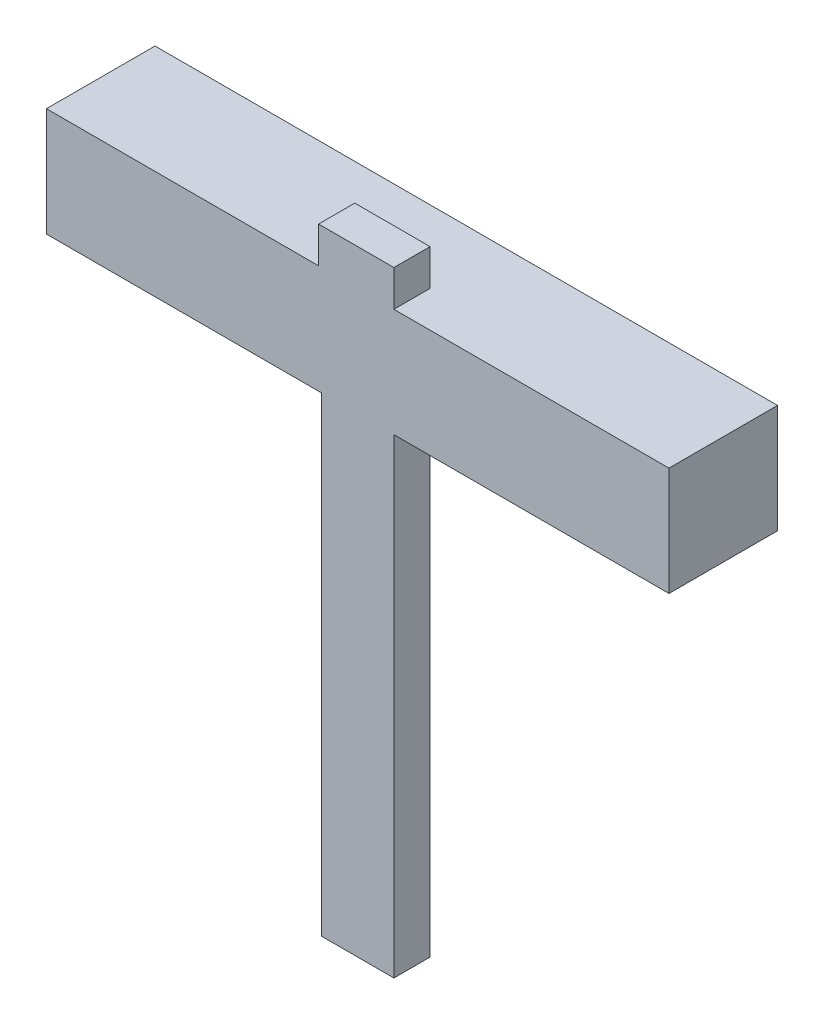
SolidWorks part; units mm, degrees
ref_plane "Front Plane" through (0, 0, 0) normal (0, 0, 1) x (1, 0, 0)
ref_plane "Top Plane" through (0, 0, 0) normal (0, 1, 0) x (1, 0, 0)
ref_plane "Right Plane" through (0, 0, 0) normal (1, 0, 0) x (0, 0, -1)
sketch "Sketch1" plane through (0, 0, 0) normal (0, 0, 1) x (1, 0, 0)
  line L0 (5, 0) -> (40, 0) construction
  line L1 (40, 0) -> (5, 0) construction
  line L2 (-5, 0) -> (-40, 0) construction
  line L3 (0, 0) -> (0, 5) construction
  line L4 (-40, 0) -> (-40, 10) construction
  line L5 (0, 0) -> (0, -65) construction
  line L6 (-5, 10) -> (-5, -65) construction
  line L7 (-40, 10) -> (40, 10)
  line L8 (-40, 10) -> (-40, 0)
  line L9 (-40, 0) -> (-5, 0)
  line L10 (40, 10) -> (40, 0)
  line L12 (5, 0) -> (40, 0)
  line L14 (-5, 0) -> (-5, -65)
  line L16 (5, 0) -> (5, -65)
  line L17 (-5, -65) -> (5, -65)
  dimension "D1" = 40
  dimension "D2" = 40
  dimension "D3" = 5
  dimension "D4" = 10
  dimension "D6" = 5
  dimension "D8" = 75
extrude "Boss-Extrude1" add sketch "Sketch1" along normal blind 5
sketch "Sketch2" plane through (0, 10, 0) normal (0, 1, 0) x (1, 0, 0)
  line L1 (-40, -5) -> (40, -5)
  line L2 (-40, -5) -> (-40, 10)
  line L3 (-40, 10) -> (40, 10)
  line L4 (40, -5) -> (40, 10)
  dimension "D1" = 15
  dimension "D2" = 80
extrude "Boss-Extrude2" add sketch "Sketch2" along normal blind 5
sketch "Sketch3" plane through (40, 0, 0) normal (1, 0, 0) x (0, 0, -1)
  line L1 (-5, 15) -> (10, 15)
  line L2 (-5, 15) -> (-5, 0)
  line L3 (-5, 0) -> (10, 0)
  line L4 (10, 15) -> (10, 0)
  dimension "D1" = 15
extrude "Boss-Extrude3" add sketch "Sketch3" along normal blind 3
sketch "Sketch4" plane through (-40, 0, 0) normal (-1, 0, 0) x (0, 0, 1)
  line L1 (-10, 15) -> (5, 15)
  line L2 (-10, 15) -> (-10, 0)
  line L3 (-10, 0) -> (5, 0)
  line L4 (5, 15) -> (5, 0)
extrude "Boss-Extrude4" add sketch "Sketch4" along normal blind 3
sketch "Sketch5" plane through (0, 0, 0) normal (0, -1, 0) x (1, 0, 0)
  line L0 (-40, 0) -> (-40.08, 0)
  line L1 (40, 0) -> (40.08, 0) construction
  line L3 (40, 0) -> (40.08, 0)
  line L4 (40, 0) -> (40, -10)
  line L5 (40, -10) -> (40.08, -10)
  line L6 (40.08, 0) -> (40.08, -10)
  line L7 (-40, 0) -> (-40.08, 0)
  line L8 (-40, 0) -> (-40, -10)
  line L9 (-40, -10) -> (-40.08, -10)
  line L10 (-40.08, 0) -> (-40.08, -10)
  line M5 (-43, -10) -> (-40, -10)
  line M6 (-40, -10) -> (-40, 0)
  dimension "D1" = 0.08
  dimension "D2" = 0.08
extrude "Cut-Extrude1" cut sketch "Sketch5" against normal blind 10 contours L0 L10 M5 M6 | L6 L3 L4 L5
sketch "Sketch6" plane through (0, 15, 0) normal (0, 1, 0) x (1, 0, 0)
  line L0 (0, 0) -> (0, -5) construction
  line L1 (0, -5) -> (5, -5) construction
  line L2 (5, -5) -> (-5, -5) construction
  line L3 (-5, -5) -> (-5, 0) construction
  line L5 (-5.4046, 0) -> (5, 0)
  line L6 (-5.4046, 0) -> (-5.4046, -5)
  line L7 (-5.4046, -5) -> (5, -5)
  line L8 (5, 0) -> (5, -5)
  dimension "D1" = 5
  dimension "D2" = 10
  dimension "D3" = 5
extrude "Boss-Extrude5" add sketch "Sketch6" along normal blind 5
